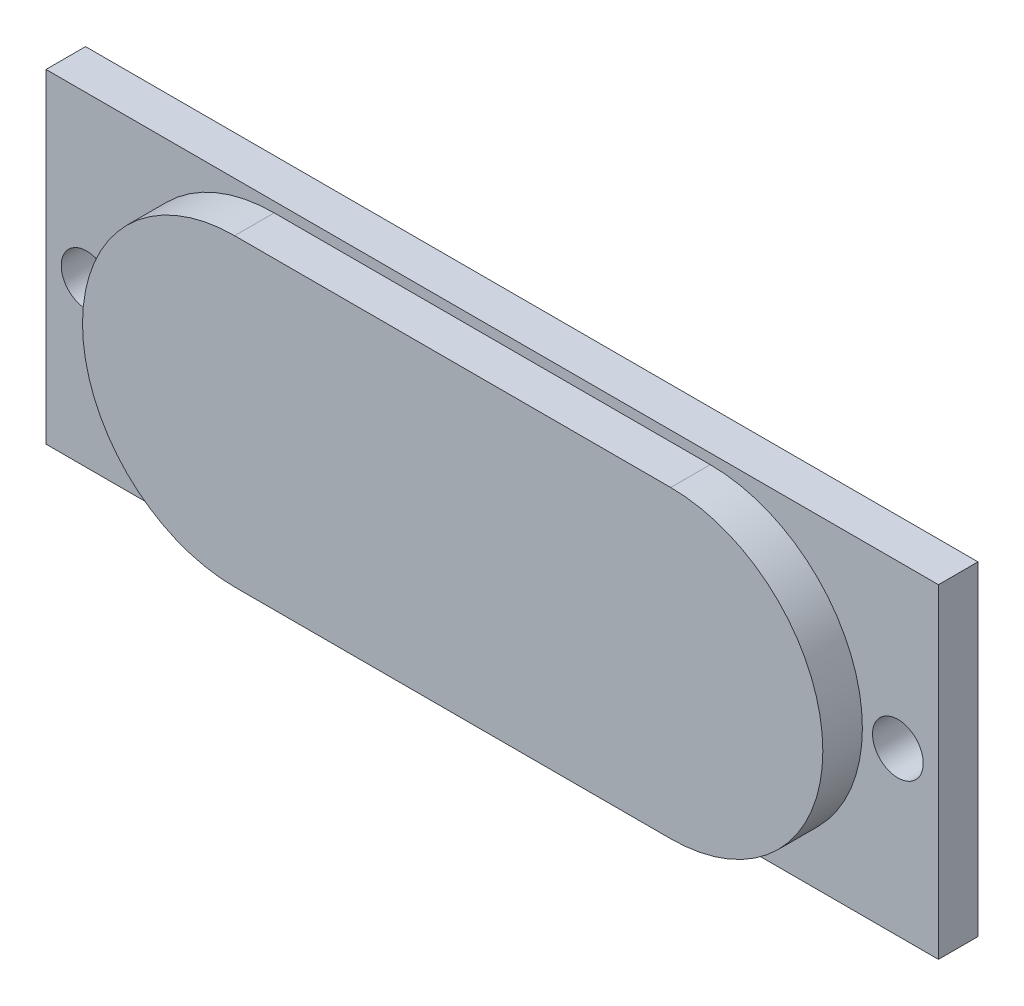
SolidWorks part; units mm, degrees
ref_plane "Front Plane" through (0, 0, 0) normal (0, 0, 1) x (1, 0, 0)
ref_plane "Top Plane" through (0, 0, 0) normal (0, 1, 0) x (1, 0, 0)
ref_plane "Right Plane" through (0, 0, 0) normal (1, 0, 0) x (0, 0, -1)
sketch "Sketch2" plane through (0, 0, 0) normal (0, 0, 1) x (1, 0, 0)
  line L0 (-55.88, 20.32) -> (55.88, 20.32)
  line L3 (27.305, 0) -> (46.355, 0) construction
  line L4 (46.355, 0) -> (50.8, 0) construction
  line L10 (-55.88, 20.32) -> (55.88, 20.32)
  line L13 (55.88, -20.32) -> (-55.88, -20.32)
  line L16 (-55.88, 20.32) -> (-55.88, -20.32)
  line L17 (-55.88, -20.32) -> (55.88, -20.32)
  line L18 (55.88, 20.32) -> (55.88, -20.32)
  line L19 (-55.88, 20.32) -> (55.88, -20.32) construction
  line L20 (-55.88, -20.32) -> (55.88, 20.32) construction
  line L21 (0, 20.32) -> (0, -20.32) construction
  line L22 (47.625, 0) -> (46.355, 0) construction
  circle A12 centre (50.8, 0) radius 3.175
  circle A13 centre (-50.8, 0) radius 3.175
  circle A14 centre (-50.8, 0) radius 3.175
  circle A15 centre (50.8, 0) radius 3.175
  point P8 (0, 0)
  dimension "D2" = 40.64
  dimension "D3" = 111.76
  dimension "D4" = 4.445
extrude "Boss-Extrude13" add sketch "Sketch2" along normal blind 4.953 contours L18 L0 L16 L13 A12 A13
sketch "Sketch3" plane through (0, 0, 4.953) normal (0, 0, 1) x (1, 0, 0)
  line L0 (27.305, 0) -> (-27.305, 0) construction
  line L1 (27.305, -19.05) -> (-27.305, -19.05)
  line L2 (27.305, 19.05) -> (-27.305, 19.05)
  arc A0 (27.305, -19.05) -> (27.305, 19.05) centre (27.305, 0) ccw
  arc A1 (-27.305, 19.05) -> (-27.305, -19.05) centre (-27.305, 0) ccw
  point P2 (0, 0)
  dimension "D1" = 54.61
  dimension "D2" = 38.1
extrude "Boss-Extrude14" add sketch "Sketch3" along normal blind 4.953 contours L2 A1 L1 A0
